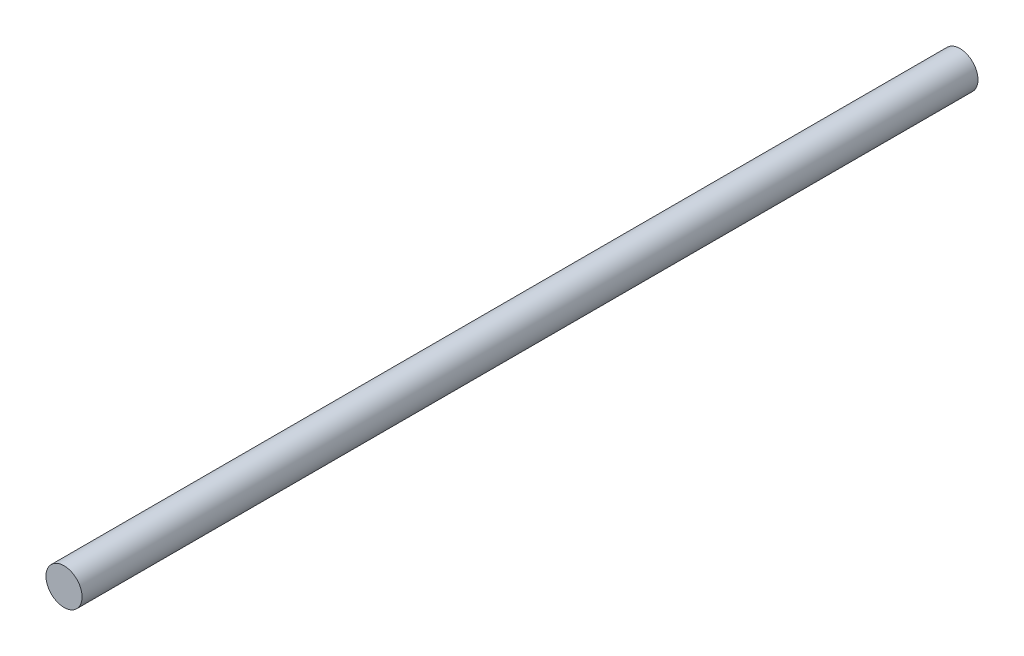
SolidWorks part; units mm, degrees
ref_plane "Front Plane" through (0, 0, 0) normal (0, 0, 1) x (1, 0, 0)
ref_plane "Top Plane" through (0, 0, 0) normal (0, 1, 0) x (1, 0, 0)
ref_plane "Right Plane" through (0, 0, 0) normal (1, 0, 0) x (0, 0, -1)
sketch "Sketch1" plane through (0, 0, 0) normal (0, 0, 1) x (1, 0, 0)
  circle A0 centre (0, 0) radius 3.175
  dimension "D1" = 6.35
extrude "Boss-Extrude1" add sketch "Sketch1" along normal blind 157.48
